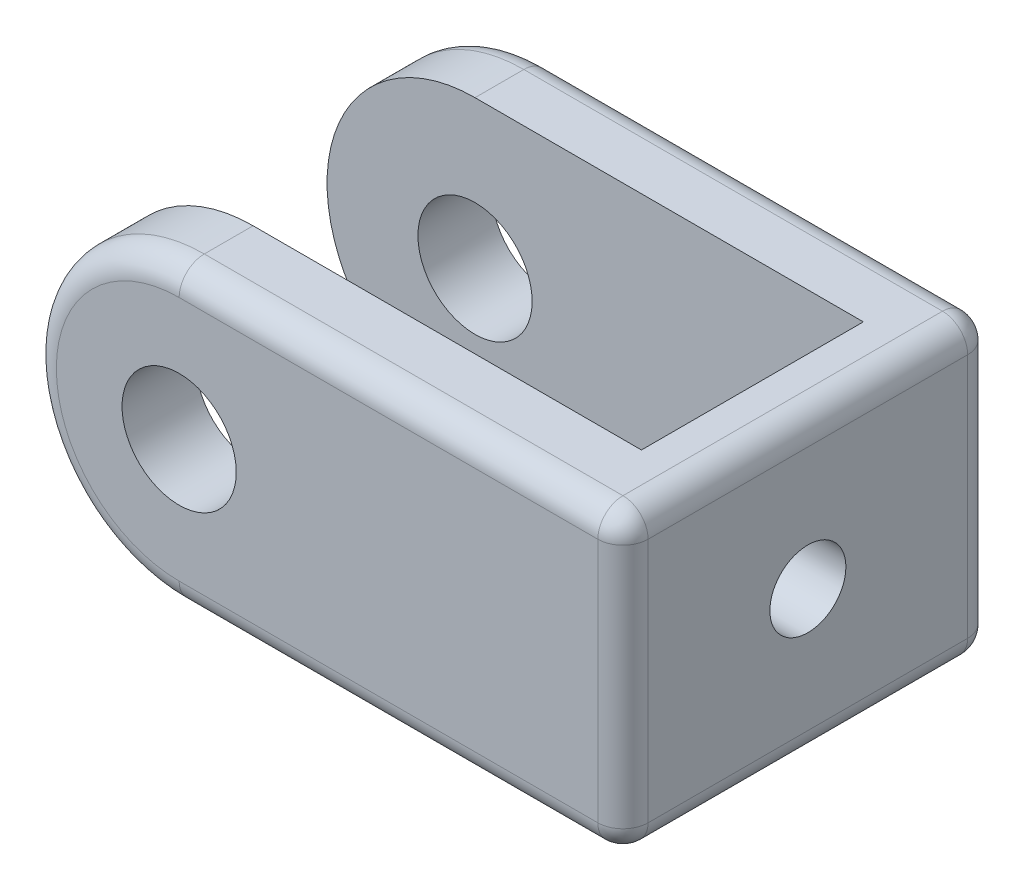
SolidWorks part; units mm, degrees
ref_plane "Front Plane" through (0, 0, 0) normal (0, 0, 1) x (1, 0, 0)
ref_plane "Top Plane" through (0, 0, 0) normal (0, 1, 0) x (1, 0, 0)
ref_plane "Right Plane" through (0, 0, 0) normal (1, 0, 0) x (0, 0, -1)
sketch "Sketch1" plane through (0, 0, 0) normal (0, 0, 1) x (1, 0, 0)
  line L0 (-19.05, 12.7) -> (19.05, 12.7)
  line L1 (19.05, 12.7) -> (19.05, -12.7)
  line L2 (19.05, -12.7) -> (-19.05, -12.7)
  arc A0 (-19.05, -12.7) -> (-19.05, 12.7) centre (-19.05, 0) cw
  point P6 (0, 12.7)
  point P9 (19.05, 0)
  dimension "D2" = 25.4
  dimension "D3" = 38.1
extrude "Boss-Extrude1" add sketch "Sketch1" along normal mid plane 31.75
sketch "Sketch3" plane through (0, 0, 15.875) normal (0, 0, 1) x (1, 0, 0)
  circle A0 centre (-19.05, 0) radius 4.9022
  arc A1 (-19.05, 12.7) -> (-19.05, -12.7) centre (-19.05, 0) ccw construction
  dimension "D1" = 9.8044
extrude "Cut-Extrude1" cut sketch "Sketch3" against normal through all
sketch "Sketch4" plane through (0, 12.7, 0) normal (0, 1, 0) x (1, 0, 0)
  line L5 (-31.75, 15.875) -> (-31.75, -15.875) construction
  line L6 (-31.75, 9.525) -> (14.2875, 9.525)
  line L7 (-31.75, 9.525) -> (-31.75, -9.525)
  line L8 (-31.75, -9.525) -> (14.2875, -9.525)
  line L9 (14.2875, 9.525) -> (14.2875, -9.525)
  line L10 (19.05, -15.875) -> (19.05, 15.875) construction
  point P2 (14.2875, 0)
  dimension "D1" = 4.7625
  dimension "D2" = 19.05
extrude "Cut-Extrude2" cut sketch "Sketch4" against normal through all
sketch "Sketch5" plane through (19.05, 0, 0) normal (1, 0, 0) x (0, 0, -1)
  line L0 (-15.875, -12.7) -> (15.875, 12.7) construction
  circle A0 centre (0, 0) radius 3.2639
  dimension "D1" = 6.5278
extrude "Cut-Extrude3" cut sketch "Sketch5" against normal up to surface (4.7625 mm away) up to face at (14.2875, 0, 0)
fillet "Fillet1" radius 2.159 10 edges at (0, -12.7, -15.875) (-31.75, 0, -15.875) (0, -12.7, 15.875) (-31.75, 0, 15.875) (0, 12.7, -15.875) (0, 12.7, 15.875) (19.05, 0, -15.875) (19.05, -12.7, 0) (19.05, 0, 15.875) (19.05, 12.7, 0)
